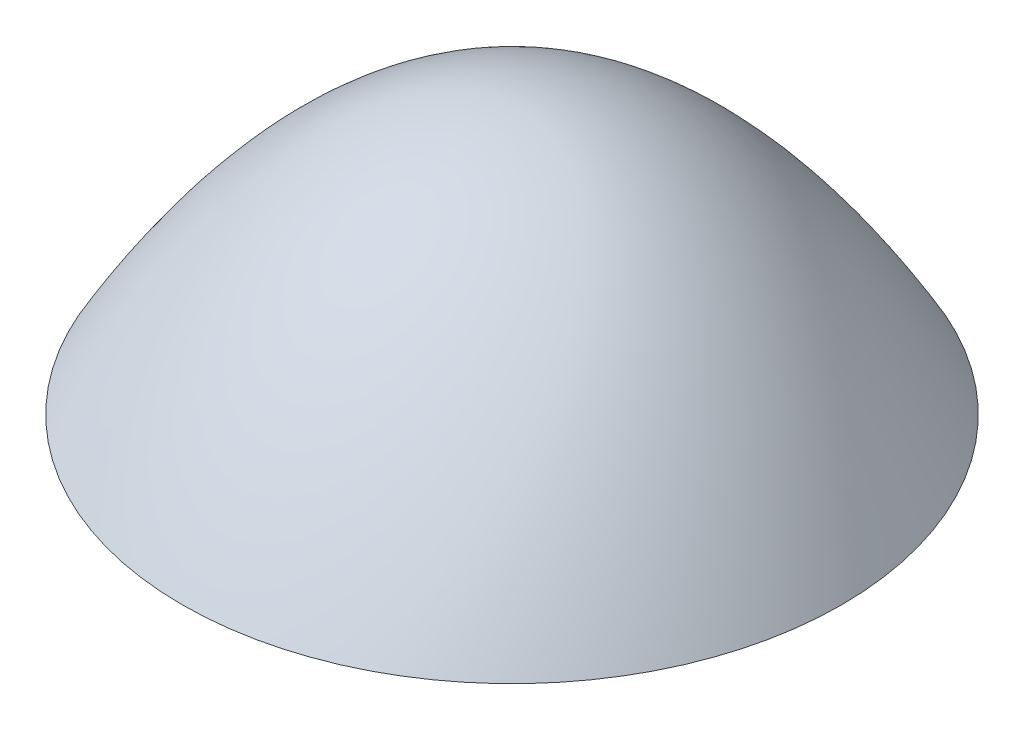
SolidWorks part; units mm, degrees
material "1060 Alloy"
ref_plane "Front Plane" through (0, 0, 0) normal (0, 0, 1) x (1, 0, 0)
ref_plane "Top Plane" through (0, 0, 0) normal (0, 1, 0) x (1, 0, 0)
ref_plane "Right Plane" through (0, 0, 0) normal (1, 0, 0) x (0, 0, -1)
sketch "Sketch1" plane through (0, 0, 0) normal (0, 0, 1) x (1, 0, 0)
  line L9 (0, 0) -> (0, 654.6147) construction
  line L12 (76.2, 150) -> (76.2, 0)
  line L13 (78.16, 150) -> (78.16, 0)
  line L14 (0, 400) -> (0, 398.04)
  line L15 (76.2, 0) -> (78.16, 0)
  ellipse E0 centre (0, 150) end of major axis (0, 398.04) minor radius 76.2 (0, 398.04) -> (76.2, 150) cw
  spline S0 degree 1 poles (0, 400) (78.16, 150) knots 0 0 1 1 construction
  spline S1 degree 3 poles (0, 400) (2.7231, 400) (8.0954, 399.1311) (15.9852, 395.3134) (23.5507, 389.1306) (33.2071, 377.8754) (44.4036, 358.3688) (56.1093, 327.0871) (65.6898, 289.0807) (71.6144, 252.9938) (74.988, 222.2996) (76.8127, 198.5857) (77.9144, 174.416) (78.16, 158.1247) (78.16, 150) knots -1.570796 -1.570796 -1.570796 -1.570796 -1.472622 -1.374447 -1.276272 -1.178097 -0.981748 -0.785398 -0.589049 -0.392699 -0.294524 -0.19635 -0.098175 0 0 0 0
  point P7 (140, 150)
  point P8 (-133.3333, 150)
  point P9 (-4.7059, 391.1765)
  dimension "D4" = 76.2
  dimension "D2" = 150
  dimension "D3" = 76.2
  dimension "D5" = 1.96
revolve "Revolve1" add sketch "Sketch1" angle 360 about L9
ref_plane "Plane1" through (0, 150, 0) normal (0, 1, 0) x (1, 0, 0)
sketch "Sketch2" plane through (0, 150, 0) normal (0, 1, 0) x (1, 0, 0)
  circle A0 centre (0, 0) radius 76.2 construction
  circle A1 centre (0, 0) radius 76.2
  circle A2 centre (0, 0) radius 74.2
  dimension "D1" = 2
extrude "Boss-Extrude1" add sketch "Sketch2" against normal blind 304.8
ref_plane "Plane2" through (0, 400, 0) normal (0, -1, 0) x (-1, 0, 0)
ref_plane "Plane3" through (0, 370, 0) normal (0, -1, 0) x (-1, 0, 0)
sketch "Sketch3" plane through (0, 370, 0) normal (0, -1, 0) x (-1, 0, 0)
  circle A0 centre (0, 0) radius 134.7473
extrude "Cut-Extrude1" cut sketch "Sketch3" along normal through all
